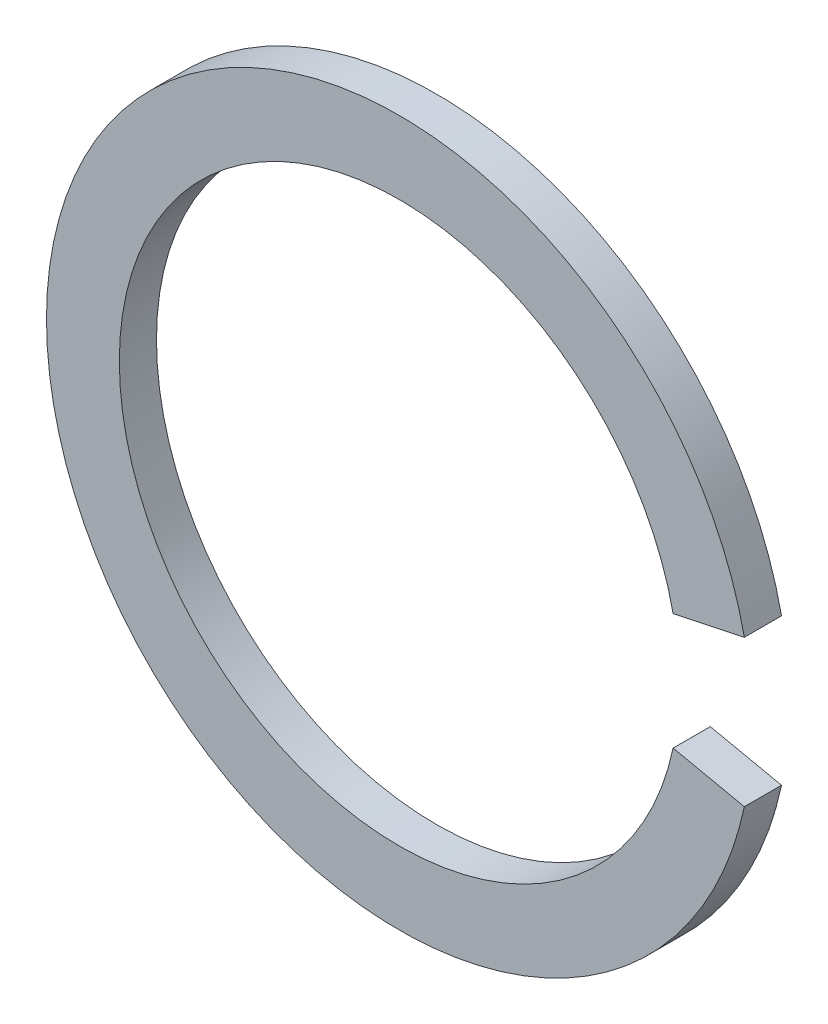
SolidWorks part; units mm, degrees
ref_plane "Front Plane" through (0, 0, 0) normal (0, 0, 1) x (1, 0, 0)
ref_plane "Top Plane" through (0, 0, 0) normal (0, 1, 0) x (1, 0, 0)
ref_plane "Right Plane" through (0, 0, 0) normal (1, 0, 0) x (0, 0, -1)
sketch "S01 - Open spring steel retainer" plane through (0, 0, 0) normal (0, 0, 1) x (1, 0, 0)
  line L0 (5.5265, 1.1747) -> (6.9644, 1.4803)
  line L1 (6.9644, -1.4803) -> (5.5265, -1.1747)
  arc A0 (6.9644, 1.4803) -> (6.9644, -1.4803) centre (0, 0) ccw
  arc A1 (5.5265, -1.1747) -> (5.5265, 1.1747) centre (0, 0) cw
  dimension "D1" = 7.12
  dimension "D2" = 5.65
  dimension "D3" = 5.5265
  dimension "D4" = 6.9644
extrude "01 - Open spring steel retainer" add sketch "S01 - Open spring steel retainer" along normal blind 0.75
